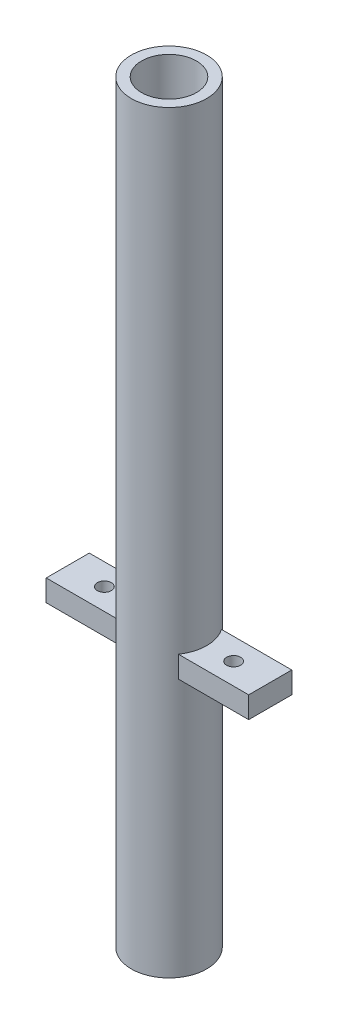
SolidWorks part; units mm, degrees
material "Plain Carbon Steel"
ref_plane "Front Plane" through (0, 0, 0) normal (0, 0, 1) x (1, 0, 0)
ref_plane "Top Plane" through (0, 0, 0) normal (0, 1, 0) x (1, 0, 0)
ref_plane "Right Plane" through (0, 0, 0) normal (1, 0, 0) x (0, 0, -1)
sketch "Sketch1" plane through (0, 0, 0) normal (0, 1, 0) x (1, 0, 0)
  circle A0 centre (0, 0) radius 12.75
  circle A1 centre (0, 0) radius 17.5
  dimension "D1" = 25.5
  dimension "D2" = 35
extrude "Boss-Extrude1" add sketch "Sketch1" along normal mid plane 350
ref_plane "Plane sets base of Plate surface - Don't move :)" through (0, -55, 0) normal (0, -1, 0) x (-1, 0, 0)
sketch "Sketch3" plane through (0, -55, 0) normal (0, -1, 0) x (-1, 0, 0)
  line L0 (0, 0) -> (0, 72.7303) construction
  line L1 (47, -10) -> (7.9096, -10)
  line L2 (47, -10) -> (47, 10)
  line L3 (47, 10) -> (7.9096, 10)
  line L4 (-47, -10) -> (-47, 10)
  line L5 (47, -10) -> (-47, 10) construction
  line L6 (47, 10) -> (-47, -10) construction
  line L7 (-7.9096, 10) -> (-47, 10)
  line L8 (-7.9096, -10) -> (-47, -10)
  circle A0 centre (0, 0) radius 12.75 construction
  arc A1 (-7.9096, 10) -> (-7.9096, -10) centre (0, 0) ccw
  circle A2 centre (-30, 0) radius 3.25
  circle A3 centre (30, 0) radius 3.25
  arc A4 (7.9096, 10) -> (7.9096, -10) centre (0, 0) cw
  point P0 (0, 0)
  dimension "D4" = 6.5
  dimension "D1" = 20
  dimension "D2" = 94
  dimension "D3" = 60
extrude "Boss-Extrude2" add sketch "Sketch3" against normal blind 10
